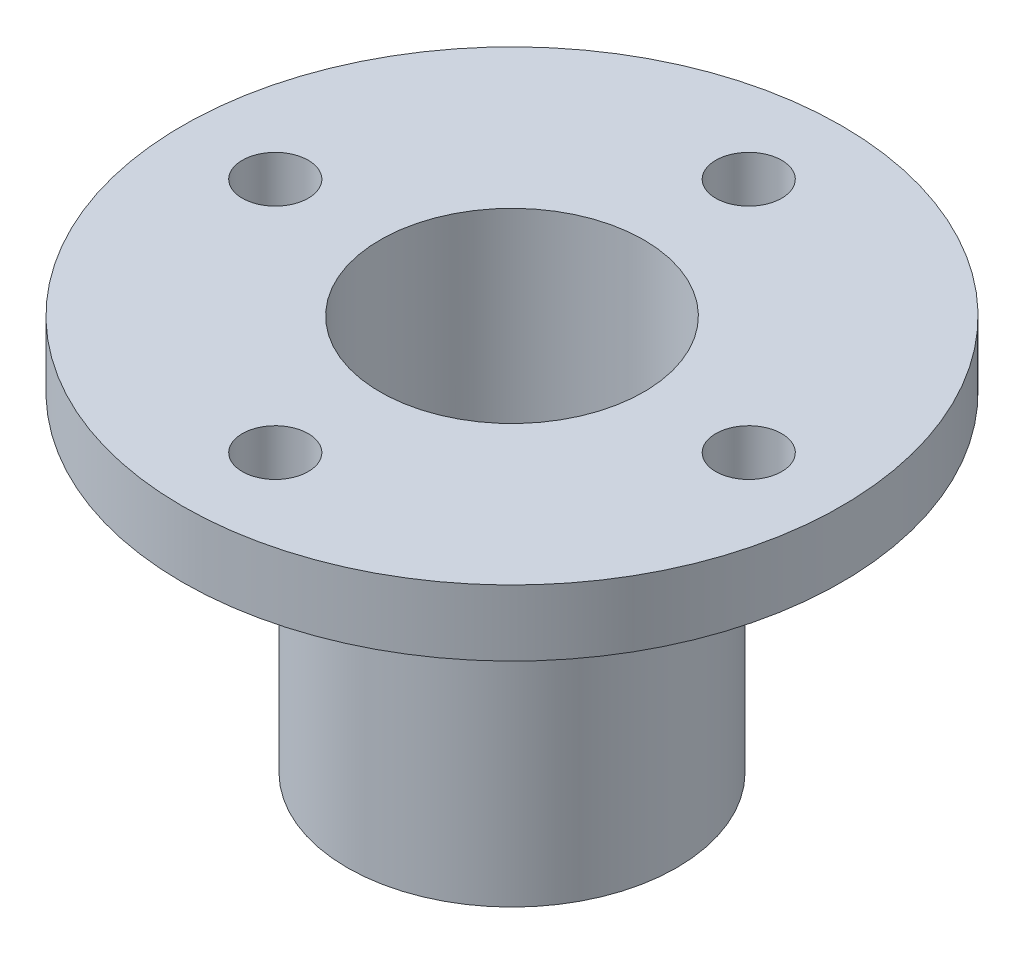
SolidWorks part; units mm, degrees
ref_plane "Front Plane" through (0, 0, 0) normal (0, 0, 1) x (1, 0, 0)
ref_plane "Top Plane" through (0, 0, 0) normal (0, 1, 0) x (1, 0, 0)
ref_plane "Right Plane" through (0, 0, 0) normal (1, 0, 0) x (0, 0, -1)
sketch "Sketch1" plane through (0, 0, 0) normal (0, 1, 0) x (1, 0, 0)
  circle A0 centre (0, 0) radius 5
  circle A1 centre (0, 0) radius 4
  dimension "D1" = 10
  dimension "D2" = 8
extrude "Boss-Extrude1" add sketch "Sketch1" along normal blind 10
sketch "Sketch2" plane through (0, 10, 0) normal (0, 1, 0) x (1, 0, 0)
  circle A0 centre (0, 0) radius 10
extrude "Boss-Extrude2" add sketch "Sketch2" along normal blind 2
sketch "Sketch3" plane through (0, 10, 0) normal (0, -1, 0) x (-1, 0, 0)
  circle A0 centre (-7.1833, 0) radius 1
  circle A1 centre (0, 7.1833) radius 1
  circle A2 centre (7.1833, 0) radius 1
  circle A3 centre (0, -7.1833) radius 1
  point P11 (0, 0)
  dimension "D1" = 4
extrude "Cut-Extrude1" cut sketch "Sketch3" against normal blind 2
sketch "Sketch4" plane through (0, 10, 0) normal (0, -1, 0) x (-1, 0, 0)
  circle A0 centre (0, 0) radius 4
extrude "Cut-Extrude2" cut sketch "Sketch4" against normal blind 2
